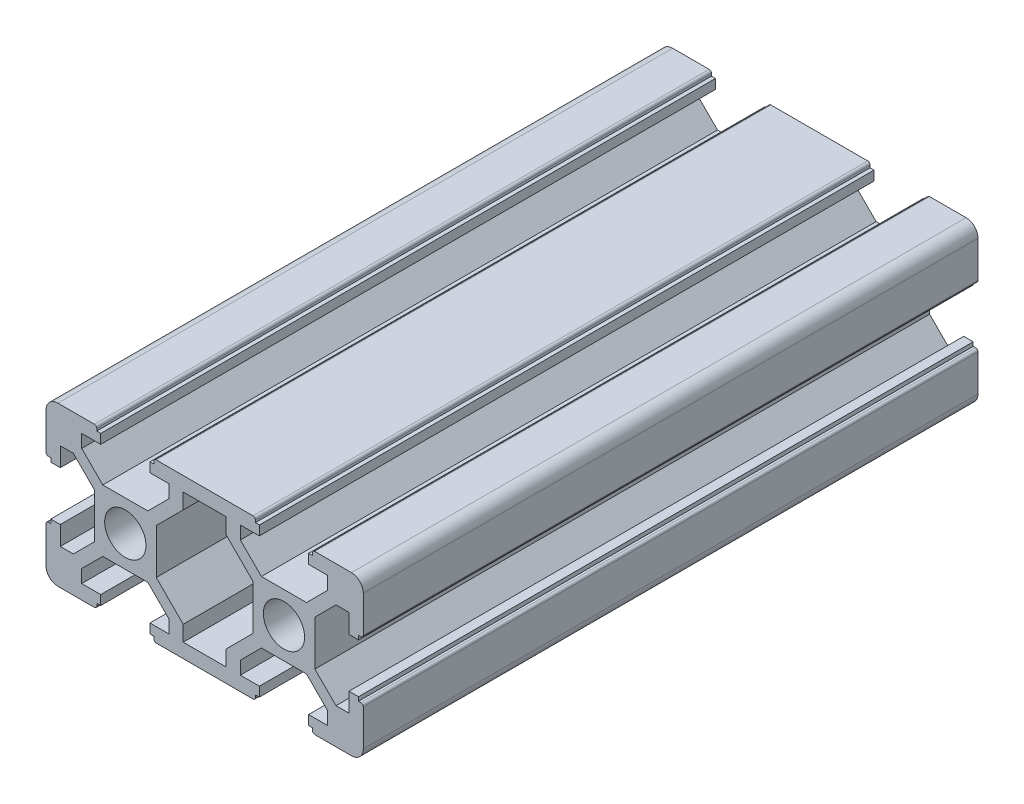
SolidWorks part; units mm, degrees
ref_plane "前视基准面" through (0, 0, 0) normal (0, 0, 1) x (1, 0, 0)
ref_plane "上视基准面" through (0, 0, 0) normal (0, 1, 0) x (1, 0, 0)
ref_plane "右视基准面" through (0, 0, 0) normal (1, 0, 0) x (0, 0, -1)
sketch "草图1" plane through (0, 0, 0) normal (0, 0, 1) x (1, 0, 0)
  line L0 (0, 0) -> (0, -41497.3383) construction
  line L1 (0, 0) -> (41497.3383, 0) construction
  line L2 (-13.9, 0) -> (-13.9, 2.8393)
  line L3 (-13.9, 2.8393) -> (-16.5607, 5.5)
  line L4 (-16.5607, 5.5) -> (-18.2, 5.5)
  line L5 (-18.2, 5.5) -> (-18.2, 3.1)
  line L6 (-18.2, 3.1) -> (-19.4, 3.1)
  line L7 (-19.4, 3.1) -> (-19.4, 3.6)
  line L8 (-19.4, 3.6) -> (-20, 3.6)
  line L9 (-20, 3.6) -> (-20, 10)
  line L10 (-20, 10) -> (-13.6, 10)
  line L11 (-13.6, 10) -> (-13.6, 9.4)
  line L12 (-13.6, 9.4) -> (-13.1, 9.4)
  line L13 (-13.1, 9.4) -> (-13.1, 8.2)
  line L14 (-13.1, 8.2) -> (-15.5, 8.2)
  line L15 (-15.5, 6.5607) -> (-12.8393, 3.9)
  line L16 (-12.8393, 3.9) -> (-7.1607, 3.9)
  line L17 (-4.5, 6.5607) -> (-7.1607, 3.9)
  line L18 (-4.5, 6.5607) -> (-4.5, 8.2)
  line L19 (-4.5, 8.2) -> (-6.9, 8.2)
  line L20 (-6.9, 8.2) -> (-6.9, 9.4)
  line L21 (-6.9, 9.4) -> (-6.4, 9.4)
  line L22 (-6.4, 9.4) -> (-6.4, 10)
  line L23 (-6.4, 10) -> (6.4, 10)
  line L24 (-15.5, 8.2) -> (-15.5, 6.5607)
  line L25 (-10, 0) -> (-20, 10) construction
  line L26 (-6.1, -2.8393) -> (-6.1, 2.8393)
  line L27 (-6.1, 2.8393) -> (-2.7, 6.2393)
  line L28 (-2.7, 6.2393) -> (-2.7, 8.2)
  line L29 (-2.7, 8.2) -> (2.7, 8.2)
  line L30 (-10, 0) -> (0, 10) construction
  line L31 (13.9, 0) -> (13.9, 2.8393)
  line L32 (6.1, -2.8393) -> (6.1, 2.8393)
  line L33 (4.5, 6.5607) -> (7.1607, 3.9)
  line L34 (12.8393, 3.9) -> (7.1607, 3.9)
  line L35 (6.1, 2.8393) -> (2.7, 6.2393)
  line L36 (2.7, 6.2393) -> (2.7, 8.2)
  line L37 (4.5, 6.5607) -> (4.5, 8.2)
  line L38 (6.4, 9.4) -> (6.4, 10)
  line L39 (6.9, 9.4) -> (6.4, 9.4)
  line L40 (6.9, 8.2) -> (6.9, 9.4)
  line L41 (4.5, 8.2) -> (6.9, 8.2)
  line L42 (13.1, 9.4) -> (13.1, 8.2)
  line L43 (13.6, 9.4) -> (13.1, 9.4)
  line L44 (13.6, 10) -> (13.6, 9.4)
  line L45 (20, 10) -> (13.6, 10)
  line L46 (20, 3.6) -> (20, 10)
  line L47 (19.4, 3.6) -> (20, 3.6)
  line L48 (19.4, 3.1) -> (19.4, 3.6)
  line L49 (18.2, 3.1) -> (19.4, 3.1)
  line L50 (18.2, 5.5) -> (18.2, 3.1)
  line L51 (16.5607, 5.5) -> (18.2, 5.5)
  line L52 (13.9, 2.8393) -> (16.5607, 5.5)
  line L53 (15.5, 6.5607) -> (12.8393, 3.9)
  line L54 (15.5, 8.2) -> (15.5, 6.5607)
  line L55 (13.1, 8.2) -> (15.5, 8.2)
  line L56 (15.5, -6.5607) -> (12.8393, -3.9)
  line L57 (13.9, -2.8393) -> (16.5607, -5.5)
  line L58 (16.5607, -5.5) -> (18.2, -5.5)
  line L59 (18.2, -5.5) -> (18.2, -3.1)
  line L60 (18.2, -3.1) -> (19.4, -3.1)
  line L61 (19.4, -3.1) -> (19.4, -3.6)
  line L62 (19.4, -3.6) -> (20, -3.6)
  line L63 (12.8393, -3.9) -> (7.1607, -3.9)
  line L64 (13.9, 0) -> (13.9, -2.8393)
  line L65 (13.1, -8.2) -> (15.5, -8.2)
  line L66 (15.5, -8.2) -> (15.5, -6.5607)
  line L67 (20, -3.6) -> (20, -10)
  line L68 (20, -10) -> (13.6, -10)
  line L69 (13.6, -10) -> (13.6, -9.4)
  line L70 (13.6, -9.4) -> (13.1, -9.4)
  line L71 (13.1, -9.4) -> (13.1, -8.2)
  line L72 (4.5, -8.2) -> (6.9, -8.2)
  line L73 (6.9, -8.2) -> (6.9, -9.4)
  line L74 (6.9, -9.4) -> (6.4, -9.4)
  line L75 (6.4, -9.4) -> (6.4, -10)
  line L76 (4.5, -6.5607) -> (4.5, -8.2)
  line L77 (2.7, -6.2393) -> (2.7, -8.2)
  line L78 (6.1, -2.8393) -> (2.7, -6.2393)
  line L79 (4.5, -6.5607) -> (7.1607, -3.9)
  line L80 (-2.7, -8.2) -> (2.7, -8.2)
  line L81 (-2.7, -6.2393) -> (-2.7, -8.2)
  line L82 (-6.1, -2.8393) -> (-2.7, -6.2393)
  line L83 (-4.5, -6.5607) -> (-7.1607, -3.9)
  line L84 (-4.5, -8.2) -> (-6.9, -8.2)
  line L85 (-4.5, -6.5607) -> (-4.5, -8.2)
  line L86 (-6.4, -10) -> (6.4, -10)
  line L87 (-6.4, -9.4) -> (-6.4, -10)
  line L88 (-6.9, -9.4) -> (-6.4, -9.4)
  line L89 (-6.9, -8.2) -> (-6.9, -9.4)
  line L90 (-13.1, -9.4) -> (-13.1, -8.2)
  line L91 (-13.6, -9.4) -> (-13.1, -9.4)
  line L92 (-13.6, -10) -> (-13.6, -9.4)
  line L93 (-15.5, -8.2) -> (-15.5, -6.5607)
  line L94 (-13.1, -8.2) -> (-15.5, -8.2)
  line L95 (-12.8393, -3.9) -> (-7.1607, -3.9)
  line L96 (-15.5, -6.5607) -> (-12.8393, -3.9)
  line L97 (-13.9, 0) -> (-13.9, -2.8393)
  line L98 (-13.9, -2.8393) -> (-16.5607, -5.5)
  line L99 (-19.4, -3.6) -> (-20, -3.6)
  line L100 (-19.4, -3.1) -> (-19.4, -3.6)
  line L101 (-18.2, -3.1) -> (-19.4, -3.1)
  line L102 (-18.2, -5.5) -> (-18.2, -3.1)
  line L103 (-16.5607, -5.5) -> (-18.2, -5.5)
  line L104 (-20, -3.6) -> (-20, -10)
  line L105 (-20, -10) -> (-13.6, -10)
  circle A0 centre (-10, 0) radius 2.6
  circle A1 centre (10, 0) radius 2.6
  point P50 (0, 8.2)
  point P95 (6.1, 0)
  point P96 (-6.1, 0)
  dimension "D1" = 5.2
  dimension "D2" = 45
  dimension "D3" = 1.5
  dimension "D4" = 20
  dimension "D5" = 40
  dimension "D6" = 0.75
  dimension "D7" = 7.2
  dimension "D8" = 6.2
  dimension "D9" = 6.1
  dimension "D10" = 1.8
  dimension "D11" = 1.2
  dimension "D12" = 12.2
  dimension "D13" = 5.4
  dimension "D14" = 11
  dimension "D15" = 1.5
  dimension "D16" = 0.75
extrude "凸台-拉伸1" add sketch "草图1" along normal mid plane 77.5
fillet "圆角1" radius 1.5 4 edges at (20, -10, 0) (20, 10, 0) (-20, -10, 0) (-20, 10, 0)
fillet "圆角2" radius 0.3 12 edges at (-6.4, 10, 0) (-13.6, 10, 0) (-20, 3.6, 0) (-20, -3.6, 0) (-13.6, -10, 0) (-6.4, -10, 0) (6.4, -10, 0) (20, -3.6, 0) (20, 3.6, 0) (13.6, -10, 0) (13.6, 10, 0) (6.4, 10, 0)
equation "\"D6@草图1\"=1/2*\"D3@草图1\""
equation "\"D16@草图1\"=0.5*\"D15@草图1\""
